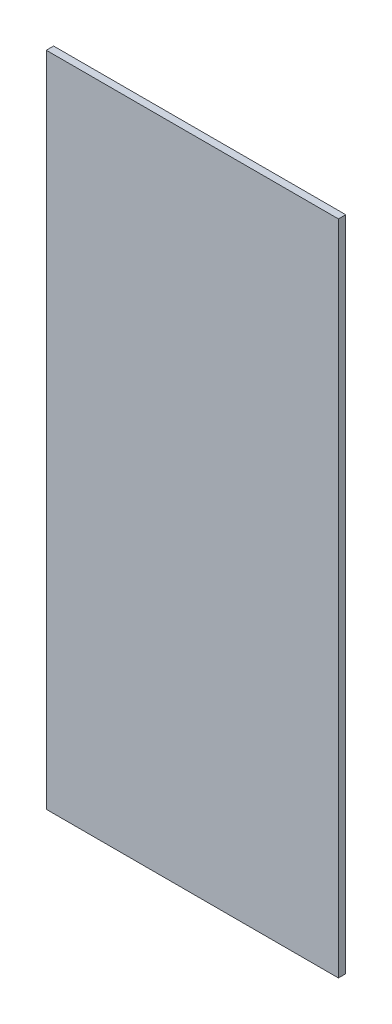
SolidWorks part; units mm, degrees
ref_plane "Front Plane" through (0, 0, 0) normal (0, 0, 1) x (1, 0, 0)
ref_plane "Top Plane" through (0, 0, 0) normal (0, 1, 0) x (1, 0, 0)
ref_plane "Right Plane" through (0, 0, 0) normal (1, 0, 0) x (0, 0, -1)
sketch "Sketch1" plane through (0, 0, 0) normal (0, 0, 1) x (1, 0, 0)
  line L1 (0, 0) -> (101.6, 0)
  line L2 (0, 0) -> (0, 228.6)
  line L3 (0, 228.6) -> (101.6, 228.6)
  line L4 (101.6, 0) -> (101.6, 228.6)
  dimension "D1" = 101.6
  dimension "D2" = 228.6
extrude "Boss-Extrude1" add sketch "Sketch1" along normal blind 2.54 contours L3 L4 L1 L2
